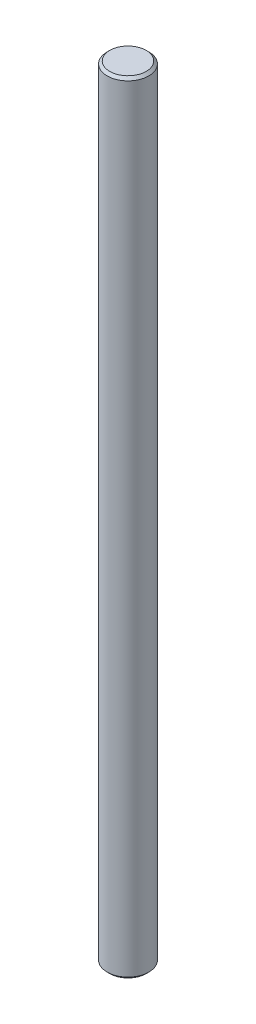
SolidWorks part; units mm, degrees
ref_plane "Спереди" through (0, 0, 0) normal (0, 0, 1) x (1, 0, 0)
ref_plane "Сверху" through (0, 0, 0) normal (0, 1, 0) x (1, 0, 0)
ref_plane "Справа" through (0, 0, 0) normal (1, 0, 0) x (0, 0, -1)
sketch "Эскиз1" plane through (0, 0, 0) normal (0, 1, 0) x (1, 0, 0)
  circle A0 centre (0, 0) radius 4
  dimension "D1" = 8
extrude "Бобышка-Вытянуть1" add sketch "Эскиз1" along normal blind 150
chamfer "Фаска1" distance 0.5 angle 45 2 edges at (0, 150, 4) (0, 0, 4)
